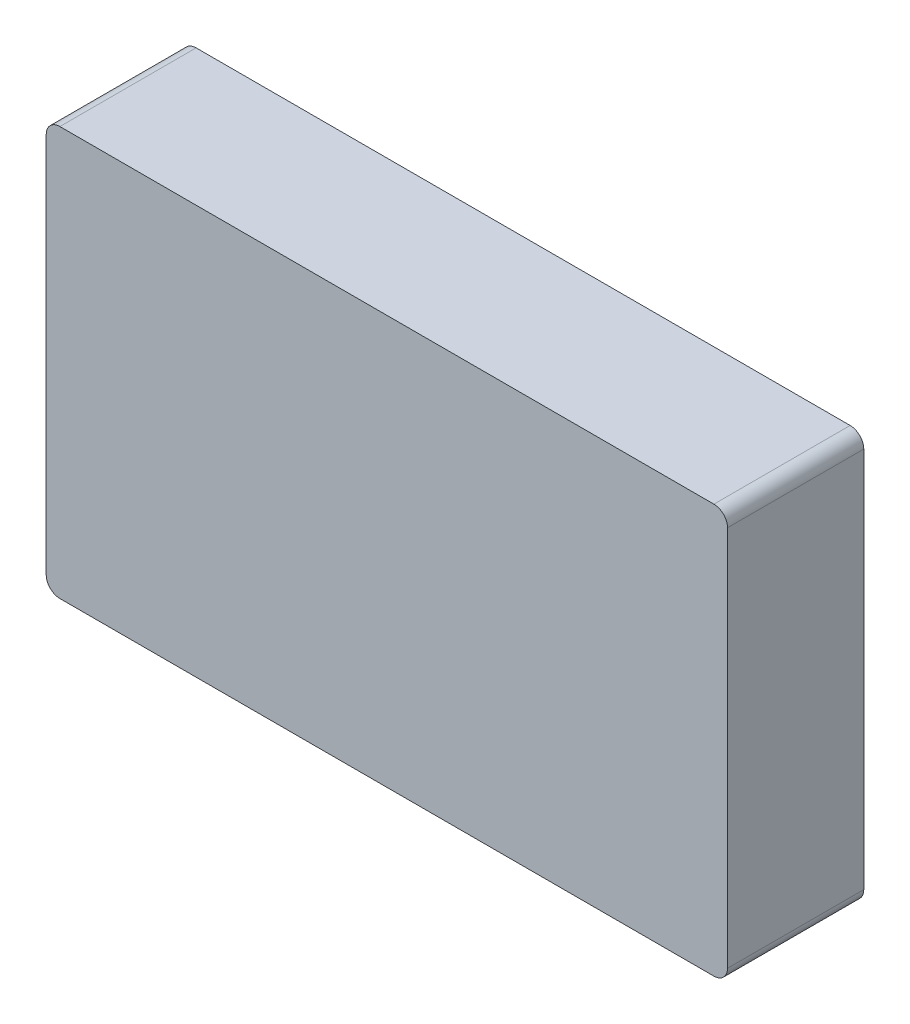
SolidWorks part; units mm, degrees
ref_plane "Plan de face" through (0, 0, 0) normal (0, 0, 1) x (1, 0, 0)
ref_plane "Plan de dessus" through (0, 0, 0) normal (0, 1, 0) x (1, 0, 0)
ref_plane "Plan de droite" through (0, 0, 0) normal (1, 0, 0) x (0, 0, -1)
sketch "Esquisse1" plane through (0, 0, 0) normal (0, 0, 1) x (1, 0, 0)
  line L0 (0, 0) -> (0, 15)
  line L1 (0, 15) -> (25, 15)
  line L2 (25, 15) -> (25, 0)
  line L3 (25, 0) -> (0, 0)
  dimension "D1" = 25
  dimension "D2" = 15
extrude "Boss.-Extru.1" add sketch "Esquisse1" along normal blind 5
fillet "Congé1" radius 0.5 4 edges at (25, 0, 2.5) (0, 0, 2.5) (0, 15, 2.5) (25, 15, 2.5)
